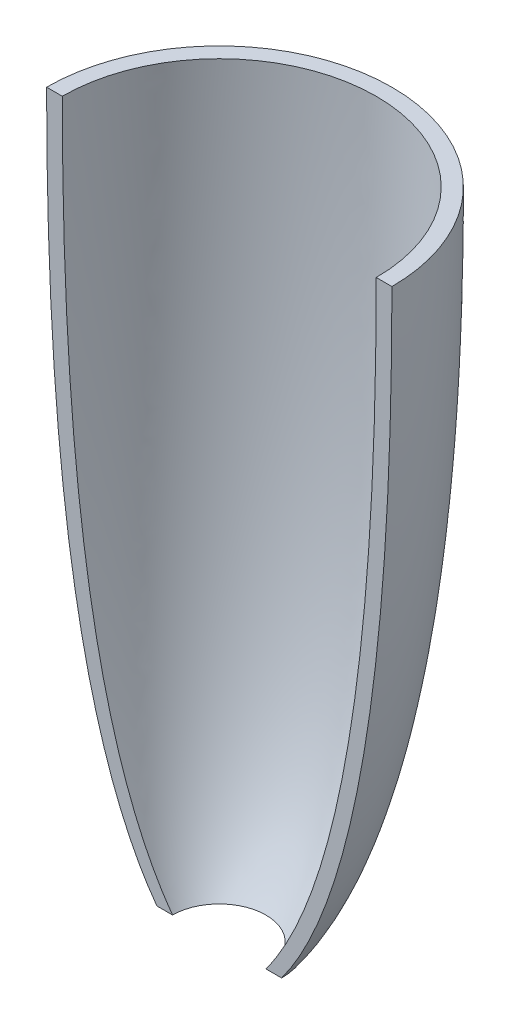
SolidWorks part; units mm, degrees
ref_plane "Спереди" through (0, 0, 0) normal (0, 0, 1) x (1, 0, 0)
ref_plane "Сверху" through (0, 0, 0) normal (0, 1, 0) x (1, 0, 0)
ref_plane "Справа" through (0, 0, 0) normal (1, 0, 0) x (0, 0, -1)
other "Configuration Table"
sketch "Sketch2" plane through (0, 0, 0) normal (0, 0, 1) x (1, 0, 0)
  line L2 (0, 0) -> (0, 134.9827) construction
  line L3 (32.9997, 124.9954) -> (29.9997, 124.9954)
  line L4 (11.9179, -0.0001) -> (8.9179, -0.0001)
  spline S0 degree 4 poles (29.9145, 137.5331) (29.9158, 137.4246) (29.9184, 137.2183) (29.9234, 136.8974) (29.9331, 135.9745) (29.95, 134.7519) (29.9707, 132.1843) (29.9896, 130.0584) (29.9999, 126.347) (30.0008, 124.3821) (29.9944, 121.4928) (29.9826, 119.425) (29.9647, 117.0751) (29.9404, 114.8697) (29.902, 112.0311) (29.8229, 107.5377) (29.6975, 102.4597) (29.5082, 96.8343) (29.2151, 90.0777) (28.8518, 83.3286) (28.392, 76.5823) (27.8212, 69.8465) (27.1504, 63.119) (26.3712, 56.4034) (25.316, 48.8266) (24.0186, 41.2873) (22.7037, 34.898) (21.4548, 29.6487) (20.2907, 25.2941) (19.0317, 21.1212) (17.7471, 17.3509) (16.5938, 14.332) (15.6379, 12.0434) (14.9525, 10.5083) (14.4845, 9.5033) (14.0887, 8.6818) (13.772, 8.041) (13.4019, 7.3113) (12.9753, 6.4956) (12.4865, 5.5953) (11.9313, 4.6158) (11.3706, 3.6703) (10.8088, 2.7637) (10.3172, 2.0056) (9.9132, 1.4038) (9.5712, 0.9098) (9.3261, 0.5617) (8.988, 0.0936) (8.7455, -0.2344) (8.2846, -0.8453) (7.9953, -1.2087) (7.6477, -1.6443) (7.4569, -1.873) (7.3484, -2.0037) (7.2926, -2.0707) knots 0 0 0 0 0 0.00273 0.00546 0.01092 0.02184 0.043681 0.065521 0.087361 0.103066 0.118771 0.134476 0.150181 0.165886 0.181591 0.213001 0.27582 0.30723 0.33864 0.401458 0.464277 0.495687 0.527097 0.589916 0.652735 0.708909 0.740318 0.771728 0.803137 0.834547 0.861799 0.882739 0.893209 0.903679 0.908661 0.913644 0.918626 0.923609 0.931462 0.939314 0.947167 0.955019 0.962064 0.969108 0.972249 0.97539 0.97853 0.981671 0.986253 0.990836 0.995418 0.997709 1 1 1 1 1 construction
  spline S1 degree 4 poles (29.9997, 124.9954) (29.9997, 124.4916) (29.9988, 123.467) (29.9944, 121.4928) (29.9826, 119.425) (29.9647, 117.0751) (29.9404, 114.8697) (29.902, 112.0311) (29.8229, 107.5377) (29.6975, 102.4597) (29.5082, 96.8343) (29.2151, 90.0777) (28.8518, 83.3286) (28.392, 76.5823) (27.8212, 69.8465) (27.1504, 63.119) (26.3712, 56.4034) (25.316, 48.8266) (24.0186, 41.2873) (22.7037, 34.898) (21.4548, 29.6487) (20.2907, 25.2941) (19.0317, 21.1212) (17.7471, 17.3509) (16.5938, 14.332) (15.6379, 12.0434) (14.9525, 10.5083) (14.4845, 9.5033) (14.0887, 8.6818) (13.772, 8.041) (13.4019, 7.3113) (12.9753, 6.4956) (12.4865, 5.5953) (11.9313, 4.6158) (11.3706, 3.6703) (10.8088, 2.7637) (10.3172, 2.0056) (9.9132, 1.4038) (9.5712, 0.9098) (9.3261, 0.5617) (9.0986, 0.2468) (8.9776, 0.0811) (8.9179, -0.0001) knots 0.087361 0.087361 0.087361 0.087361 0.087361 0.103066 0.118771 0.134476 0.150181 0.165886 0.181591 0.213001 0.27582 0.30723 0.33864 0.401458 0.464277 0.495687 0.527097 0.589916 0.652735 0.708909 0.740318 0.771728 0.803137 0.834547 0.861799 0.882739 0.893209 0.903679 0.908661 0.913644 0.918626 0.923609 0.931462 0.939314 0.947167 0.955019 0.962064 0.969108 0.972249 0.97539 0.97853 0.981671 0.981671 0.981671 0.981671 0.981671
  spline S2 degree 4 poles (32.9145, 137.5331) (32.9158, 137.4246) (32.9184, 137.2183) (32.9234, 136.8974) (32.9331, 135.9745) (32.95, 134.7519) (32.9707, 132.1843) (32.9896, 130.0584) (32.9999, 126.347) (33.0008, 124.3821) (32.9944, 121.4928) (32.9826, 119.425) (32.9647, 117.0751) (32.9404, 114.8697) (32.902, 112.0311) (32.8229, 107.5377) (32.6975, 102.4597) (32.5082, 96.8343) (32.2151, 90.0777) (31.8518, 83.3286) (31.392, 76.5823) (30.8212, 69.8465) (30.1504, 63.119) (29.3712, 56.4034) (28.316, 48.8266) (27.0186, 41.2873) (25.7037, 34.898) (24.4548, 29.6487) (23.2907, 25.2941) (22.0317, 21.1212) (20.7471, 17.3509) (19.5938, 14.332) (18.6379, 12.0434) (17.9525, 10.5083) (17.4845, 9.5033) (17.0887, 8.6818) (16.772, 8.041) (16.4019, 7.3113) (15.9753, 6.4956) (15.4865, 5.5953) (14.9313, 4.6158) (14.3706, 3.6703) (13.8088, 2.7637) (13.3172, 2.0056) (12.9132, 1.4038) (12.5712, 0.9098) (12.3261, 0.5617) (11.988, 0.0936) (11.7455, -0.2344) (11.2846, -0.8453) (10.9953, -1.2087) (10.6477, -1.6443) (10.4569, -1.873) (10.3484, -2.0037) (10.2926, -2.0707) knots 0 0 0 0 0 0.00273 0.00546 0.01092 0.02184 0.043681 0.065521 0.087361 0.103066 0.118771 0.134476 0.150181 0.165886 0.181591 0.213001 0.27582 0.30723 0.33864 0.401458 0.464277 0.495687 0.527097 0.589916 0.652735 0.708909 0.740318 0.771728 0.803137 0.834547 0.861799 0.882739 0.893209 0.903679 0.908661 0.913644 0.918626 0.923609 0.931462 0.939314 0.947167 0.955019 0.962064 0.969108 0.972249 0.97539 0.97853 0.981671 0.986253 0.990836 0.995418 0.997709 1 1 1 1 1 construction
  spline S3 degree 4 poles (32.9997, 124.9954) (32.9997, 124.4916) (32.9988, 123.467) (32.9944, 121.4928) (32.9826, 119.425) (32.9647, 117.0751) (32.9404, 114.8697) (32.902, 112.0311) (32.8229, 107.5377) (32.6975, 102.4597) (32.5082, 96.8343) (32.2151, 90.0777) (31.8518, 83.3286) (31.392, 76.5823) (30.8212, 69.8465) (30.1504, 63.119) (29.3712, 56.4034) (28.316, 48.8266) (27.0186, 41.2873) (25.7037, 34.898) (24.4548, 29.6487) (23.2907, 25.2941) (22.0317, 21.1212) (20.7471, 17.3509) (19.5938, 14.332) (18.6379, 12.0434) (17.9525, 10.5083) (17.4845, 9.5033) (17.0887, 8.6818) (16.772, 8.041) (16.4019, 7.3113) (15.9753, 6.4956) (15.4865, 5.5953) (14.9313, 4.6158) (14.3706, 3.6703) (13.8088, 2.7637) (13.3172, 2.0056) (12.9132, 1.4038) (12.5712, 0.9098) (12.3261, 0.5617) (12.0986, 0.2468) (11.9776, 0.0811) (11.9179, -0.0001) knots 0.087361 0.087361 0.087361 0.087361 0.087361 0.103066 0.118771 0.134476 0.150181 0.165886 0.181591 0.213001 0.27582 0.30723 0.33864 0.401458 0.464277 0.495687 0.527097 0.589916 0.652735 0.708909 0.740318 0.771728 0.803137 0.834547 0.861799 0.882739 0.893209 0.903679 0.908661 0.913644 0.918626 0.923609 0.931462 0.939314 0.947167 0.955019 0.962064 0.969108 0.972249 0.97539 0.97853 0.981671 0.981671 0.981671 0.981671 0.981671
revolve "Revolve1" add sketch "Sketch2" angle 180 about L2
